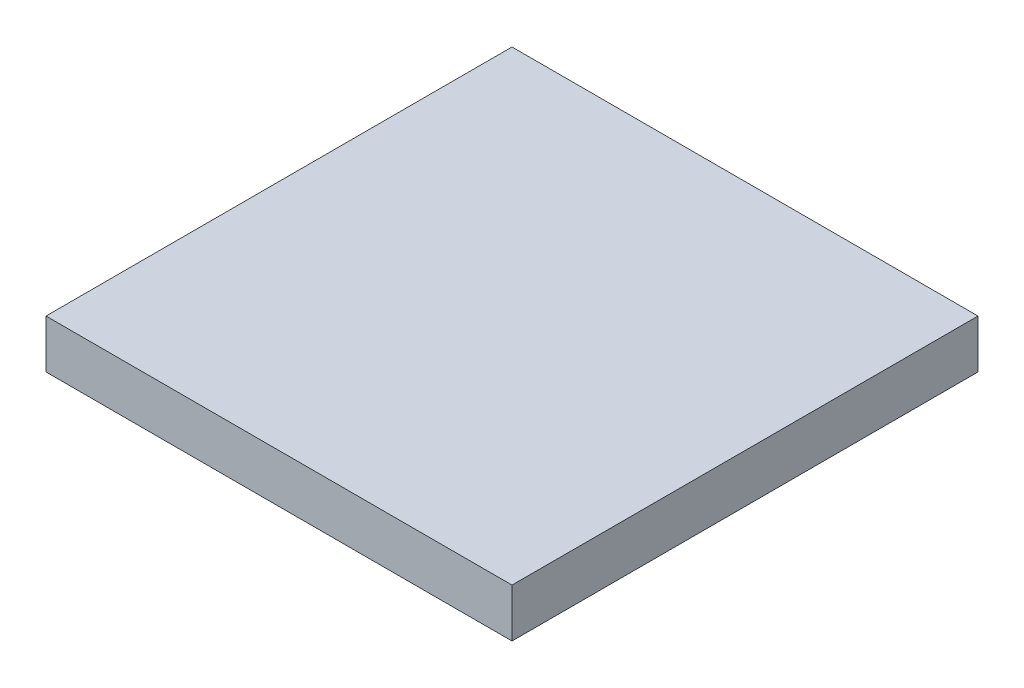
SolidWorks part; units mm, degrees
ref_plane "Front Plane" through (0, 0, 0) normal (0, 0, 1) x (1, 0, 0)
ref_plane "Top Plane" through (0, 0, 0) normal (0, 1, 0) x (1, 0, 0)
ref_plane "Right Plane" through (0, 0, 0) normal (1, 0, 0) x (0, 0, -1)
sketch "Sketch1" plane through (0, 0, 0) normal (0, 1, 0) x (1, 0, 0)
  line L1 (0, 0) -> (38.1, 0)
  line L2 (0, 0) -> (0, 38.1)
  line L3 (0, 38.1) -> (38.1, 38.1)
  line L4 (38.1, 0) -> (38.1, 38.1)
  dimension "D1" = 38.1
  dimension "D2" = 38.1
extrude "Boss-Extrude1" add sketch "Sketch1" along normal blind 3.9624
